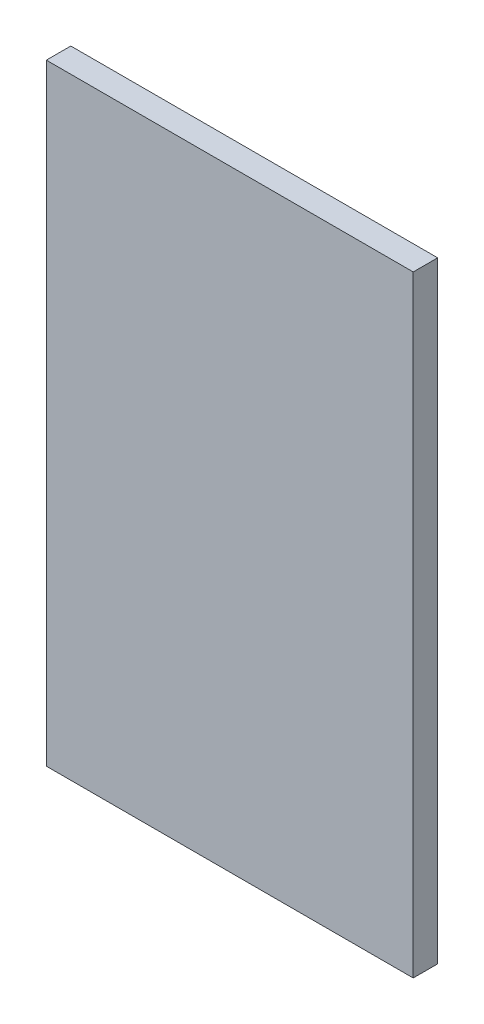
SolidWorks part; units mm, degrees
ref_plane "Front Plane" through (0, 0, 0) normal (0, 0, 1) x (1, 0, 0)
ref_plane "Top Plane" through (0, 0, 0) normal (0, 1, 0) x (1, 0, 0)
ref_plane "Right Plane" through (0, 0, 0) normal (1, 0, 0) x (0, 0, -1)
sketch "Sketch1" plane through (0, 0, 0) normal (0, 0, 1) x (1, 0, 0)
  line L1 (-22.5, -37.5) -> (22.5, -37.5)
  line L2 (-22.5, -37.5) -> (-22.5, 37.5)
  line L3 (-22.5, 37.5) -> (22.5, 37.5)
  line L4 (22.5, -37.5) -> (22.5, 37.5)
  line L5 (0, 37.5) -> (0, -37.5) construction
  line L6 (-22.5, 0) -> (22.5, 0) construction
  point P0 (0, 0)
  dimension "D1" = 75
  dimension "D2" = 45
extrude "Boss-Extrude1" add sketch "Sketch1" along normal blind 3
